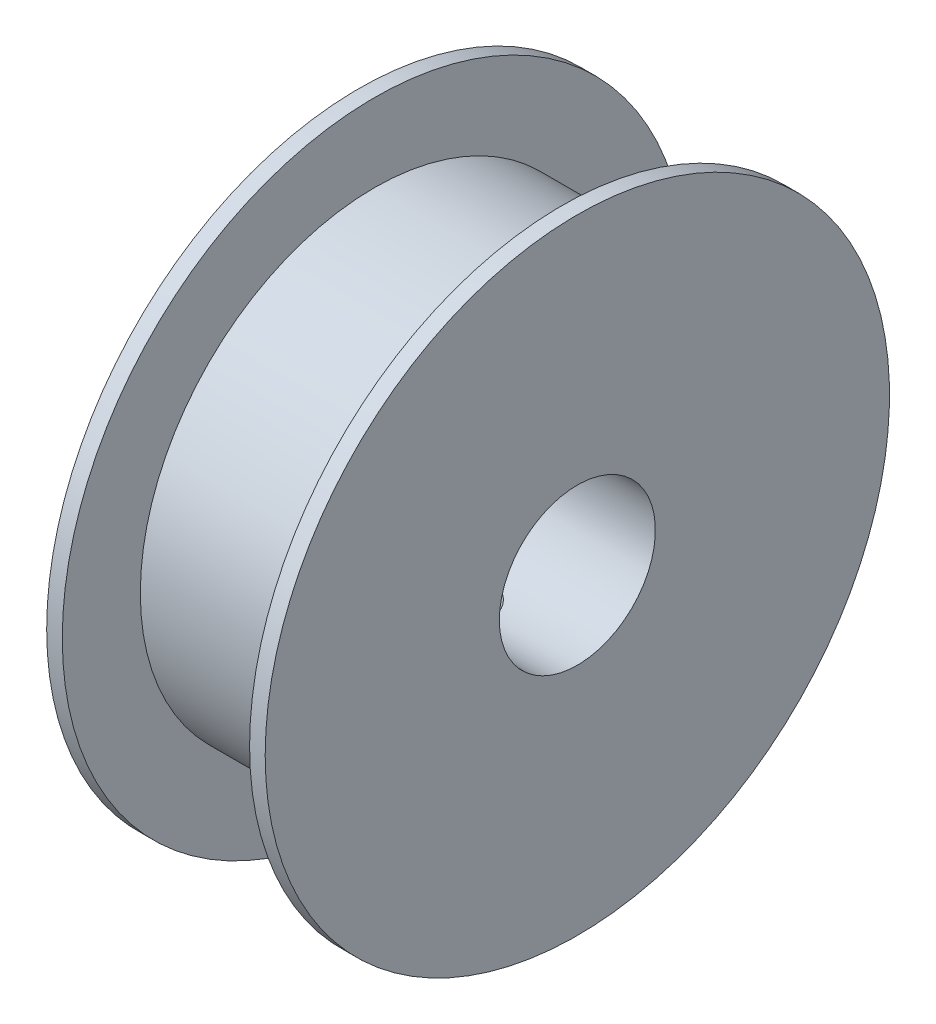
SolidWorks part; units mm, degrees
material "6061 合金"
ref_plane "正面" through (0, 0, 0) normal (0, 0, 1) x (1, 0, 0)
ref_plane "平面" through (0, 0, 0) normal (0, 1, 0) x (1, 0, 0)
ref_plane "右側面" through (0, 0, 0) normal (1, 0, 0) x (0, 0, -1)
sketch "ｽｹｯﾁ2" plane through (0, 0, 0) normal (0, 1, 0) x (1, 0, 0)
  line L0 (-44.7309, -0.056) -> (-44.7309, -15.056)
  line L1 (-44.7309, -0.056) -> (-43.7309, -0.056)
  line L2 (-43.7309, -0.056) -> (-43.7309, -5.056)
  line L3 (-43.7309, -5.056) -> (-31.7309, -5.056)
  line L4 (-31.7309, -5.056) -> (-31.7309, -0.056)
  line L5 (-31.7309, -0.056) -> (-30.7309, -0.056)
  line L6 (-30.7309, -0.056) -> (-30.7309, -15.056)
  line L7 (-30.7309, -15.056) -> (-44.7309, -15.056)
  line L8 (-49.8494, -20.056) -> (-18.0543, -20.056) construction
  dimension "D1" = 1
  dimension "D2" = 1
  dimension "D3" = 5
  dimension "D4" = 5
  dimension "D5" = 15
  dimension "D6" = 14
  dimension "D7" = 5
revolve "回転1" add sketch "ｽｹｯﾁ2" angle 360 about L8
sketch "ｽｹｯﾁ3" plane through (0, 0, 0) normal (0, 1, 0) x (1, 0, 0)
  line L1 (-43.7309, -0.056) -> (-44.7309, -0.056) construction
  line L2 (-30.7309, -40.056) -> (-30.7309, -0.056) construction
  circle A0 centre (-37.7309, -20.056) radius 1.6
  dimension "D1" = 3.2
  dimension "D2" = 20
  dimension "D3" = 7
extrude "ｶｯﾄ - 押し出し1" cut sketch "ｽｹｯﾁ3" against normal through all
